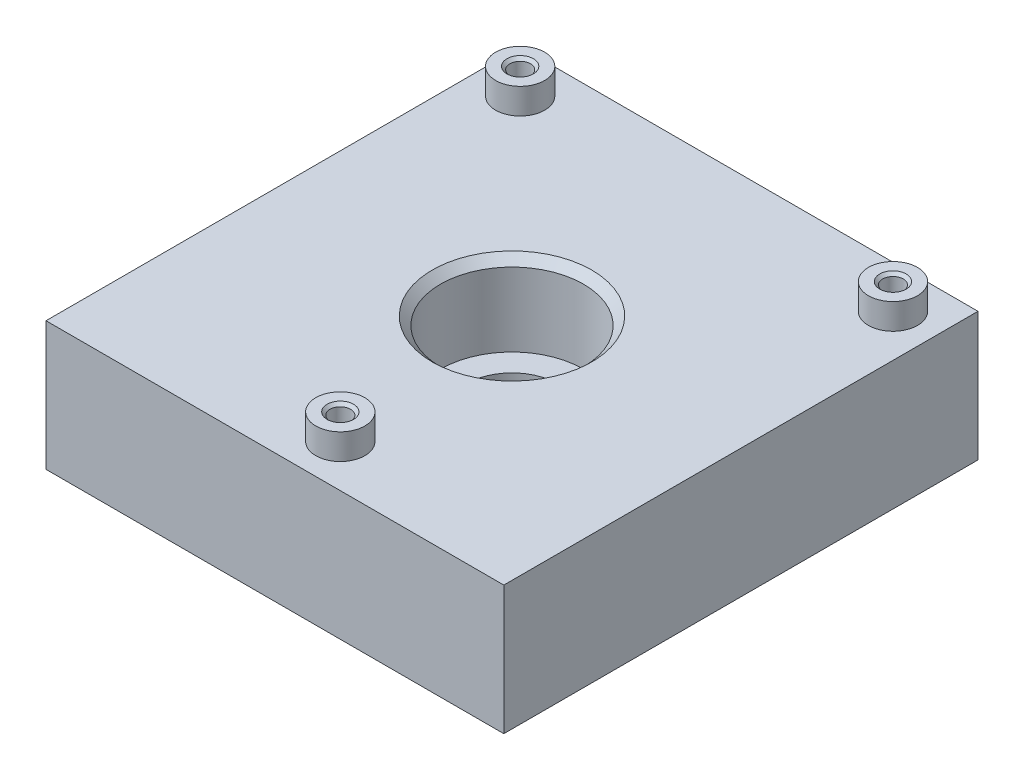
SolidWorks part; units mm, degrees
ref_plane "Front Plane" through (0, 0, 0) normal (0, 0, 1) x (1, 0, 0)
ref_plane "Top Plane" through (0, 0, 0) normal (0, 1, 0) x (1, 0, 0)
ref_plane "Right Plane" through (0, 0, 0) normal (1, 0, 0) x (0, 0, -1)
sketch "Sketch1" plane through (0, 0, 0) normal (0, 1, 0) x (1, 0, 0)
  line L1 (-17.78, 18.415) -> (17.78, 18.415)
  line L2 (-17.78, 18.415) -> (-17.78, -18.415)
  line L3 (-17.78, -18.415) -> (17.78, -18.415)
  line L4 (17.78, 18.415) -> (17.78, -18.415)
  line L5 (-17.78, 18.415) -> (17.78, -18.415) construction
  line L6 (-17.78, -18.415) -> (17.78, 18.415) construction
  point P0 (0, 0)
  dimension "D1" = 35.56
  dimension "D2" = 36.83
extrude "Boss-Extrude1" add sketch "Sketch1" along normal blind 10
hole_wizard "CBORE for 1/4 Socket Head Cap Screw1" positions "Sketch2" profile "Sketch4" counterbore size "1/4" standard "ANSI Inch" end condition through all
sketch "Sketch2" plane through (0, 10, 0) normal (0, 1, 0) x (1, 0, 0)
  point P0 (0, 0)
sketch "Sketch4" plane through (0, 10, 0) normal (1, 0, 0) x (0, 0, 1)
  line L0 (0, 0) -> (0, 10)
  line L1 (0, 10) -> (3.5712, 10)
  line L3 (3.5712, 10) -> (3.5712, 6.35)
  line L4 (5.5562, 6.35) -> (3.5712, 6.35)
  line L5 (5.5562, 6.35) -> (5.5562, 0.635)
  line L6 (5.5562, 0.635) -> (6.1913, 0)
  line L7 (6.1913, 0) -> (0, 0)
  line L8 (-5.5562, 0.635) -> (-6.1913, 0) construction
  line L11 (0, -6.35) -> (0, 107.95) construction
  dimension "Thru Hole Dia." = 7.1425
  dimension "Thru Hole Depth" = 10
  dimension "C'Bore Dia." = 11.1125
  dimension "C'Bore Depth" = 6.35
  dimension "Near C'Sink Dia." = 12.3825
  dimension "Near C'Sink Angle" = 90
sketch "Sketch5" plane through (0, 10, 0) normal (0, 1, 0) x (1, 0, 0)
  line L0 (17.78, 18.415) -> (-17.78, 18.415) construction
  line L1 (-17.78, 18.415) -> (-17.78, -18.415) construction
  line L2 (17.78, -18.415) -> (17.78, 18.415) construction
  line L3 (-17.78, -18.415) -> (17.78, -18.415) construction
  circle A0 centre (-14.478, 15.113) radius 1.905
  circle A1 centre (14.478, 15.113) radius 1.905
  circle A2 centre (1.778, -15.113) radius 1.905
  point P6 (0, 0)
  dimension "D1" = 3.81
  dimension "D2" = 3.302
  dimension "D3" = 3.302
  dimension "D4" = 3.302
  dimension "D5" = 3.302
  dimension "D6" = 16.002
extrude "Boss-Extrude2" add sketch "Sketch5" along normal blind 2
hole_wizard "M2x0.4 Tapped Hole1" positions "Sketch6" profile "Sketch8" tap size "M2x0.4" standard "ANSI Metric" end condition through all
sketch "Sketch6" plane through (0, 12, 0) normal (0, 1, 0) x (1, 0, 0)
  point P0 (-14.478, 15.113)
  point P3 (14.478, 15.113)
  point P6 (1.778, -15.113)
sketch "Sketch8" plane through (-14.478, 12, -15.113) normal (1, 0, 0) x (0, 0, 1)
  line L0 (0, 0) -> (0, 12)
  line L1 (0, 12) -> (0.8, 12)
  line L2 (0.8, 12) -> (0.8, 0.225)
  line L3 (0.8, 0.225) -> (1.025, 0)
  line L5 (1.025, 0) -> (0, 0)
  line L6 (-0.8, 0.225) -> (-1.025, 0) construction
  line L11 (0, -6.35) -> (0, 107.95) construction
  dimension "Thru Tap Drill Dia." = 1.6
  dimension "Thru Tap Drill Depth" = 12
  dimension "Near C'Sink Dia." = 2.05
  dimension "Near C'Sink Angle" = 90
cosmetic thread "Hole Thread1" parameters "D2"=2
cosmetic thread "Hole Thread2" parameters "D2"=2
cosmetic thread "Hole Thread3" parameters "D2"=2
